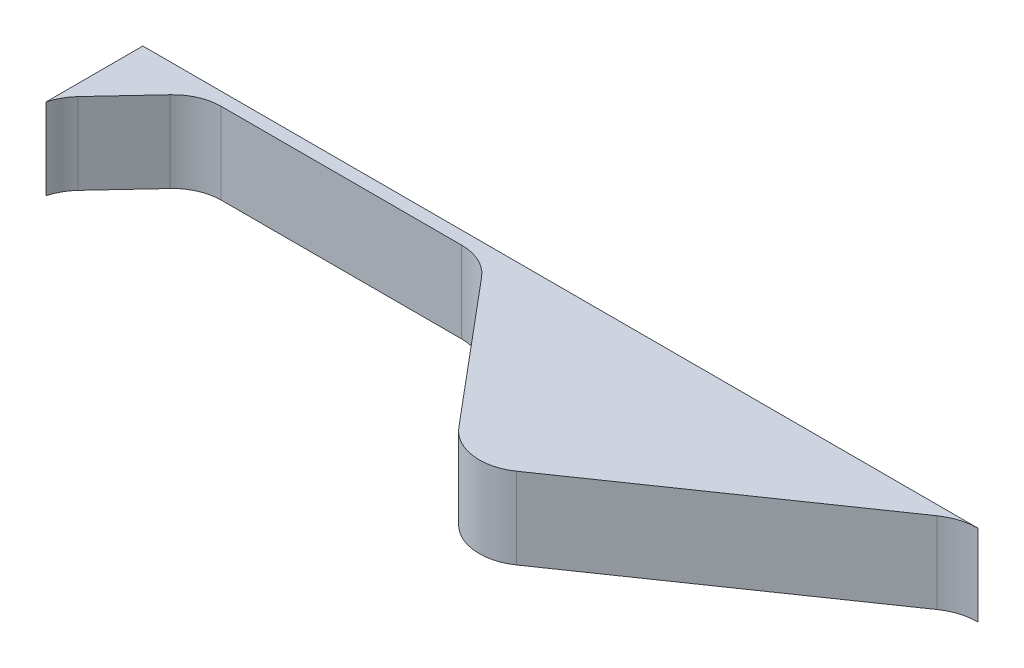
SolidWorks part; units mm, degrees
ref_plane "Front Plane" through (0, 0, 0) normal (0, 0, 1) x (1, 0, 0)
ref_plane "Top Plane" through (0, 0, 0) normal (0, 1, 0) x (1, 0, 0)
ref_plane "Right Plane" through (0, 0, 0) normal (1, 0, 0) x (0, 0, -1)
sketch "Sketch1" plane through (0, 0, 0) normal (0, 1, 0) x (1, 0, 0)
  line L0 (0, 0) -> (0, 7.5712)
  line L1 (0, 7.5712) -> (65.278, 7.5712)
  line L2 (62.8261, 6.8075) -> (43.3819, -6.6061)
  line L3 (38.1687, -5.9012) -> (28.8624, 5.1895)
  line L4 (25.9438, 6.5505) -> (7.1478, 6.5505)
  line L6 (4.3613, 5.3389) -> (0.8967, 1.6237)
  arc A0 (62.8261, 6.8075) -> (65.278, 7.5712) centre (65.278, 3.2532) cw
  arc A1 (43.3819, -6.6061) -> (38.1687, -5.9012) centre (41.1626, -3.389) cw
  arc A2 (28.8624, 5.1895) -> (25.9438, 6.5505) centre (25.9438, 2.7405) ccw
  arc A3 (7.1478, 6.5505) -> (4.3613, 5.3389) centre (7.1478, 2.7405) ccw
  arc A4 (0.8967, 1.6237) -> (0, 0) centre (3.6832, -0.9748) ccw
  dimension "D4" = 4.318
  dimension "D6" = 3.9083
  dimension "D7" = 14.478
  dimension "D8" = 3.81
  dimension "D10" = 3.81
  dimension "D16" = 3.81
  dimension "D1" = 65.278
  dimension "D5" = 23.622
  dimension "D9" = 18.796
  dimension "D11" = 47
  dimension "D12" = 34.6
  dimension "D13" = 84.6
  dimension "D14" = 50
  dimension "D15" = 5.08
extrude "Boss-Extrude1" add sketch "Sketch1" along normal blind 6.35
